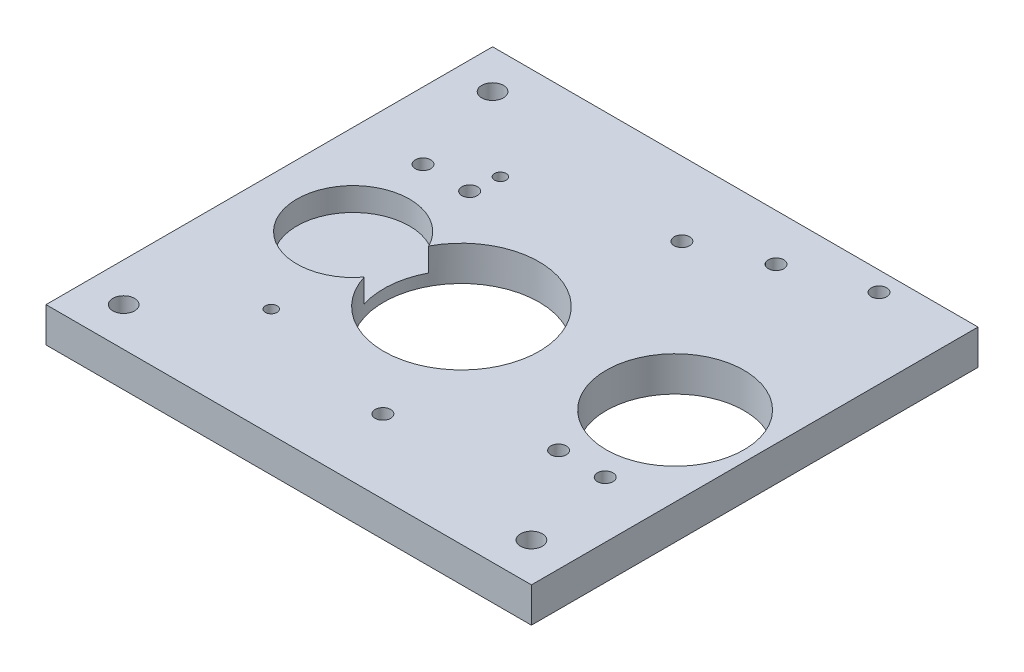
SolidWorks part; units mm, degrees
ref_plane "Front" through (0, 0, 0) normal (0, 0, 1) x (1, 0, 0)
ref_plane "Top" through (0, 0, 0) normal (0, 1, 0) x (1, 0, 0)
ref_plane "Right" through (0, 0, 0) normal (1, 0, 0) x (0, 0, -1)
sketch "Sketch1" plane through (0, 0, 0) normal (0, 1, 0) x (1, 0, 0)
  line L1 (0, 0) -> (125, 0)
  line L2 (0, 0) -> (0, 115)
  line L3 (0, 115) -> (125, 115)
  line L4 (125, 0) -> (125, 115)
  dimension "D1" = 125
  dimension "D2" = 115
extrude "Top_Base" add sketch "Sketch1" along normal blind 9
sketch "Fingers_Position" plane through (0, 9, 0) normal (0, 1, 0) x (1, 0, 0)
  line L0 (43.75, 76.5) -> (16.25, 76.5) construction
  line L1 (71.25, 60.5) -> (16.25, 60.5) construction
  line L2 (71.25, 60.5) -> (71.25, 92.5) construction
  line L3 (71.25, 92.5) -> (16.25, 92.5) construction
  line L4 (16.25, 60.5) -> (16.25, 92.5) construction
  line L5 (71.25, 22.5) -> (16.25, 22.5) construction
  line L6 (71.25, 22.5) -> (71.25, 54.5) construction
  line L7 (71.25, 54.5) -> (16.25, 54.5) construction
  line L8 (16.25, 22.5) -> (16.25, 54.5) construction
  line L9 (43.75, 92.5) -> (43.75, 60.5) construction
  line L10 (16.25, 38.5) -> (43.75, 38.5) construction
  line L12 (0, 115) -> (0, 0) construction
  line L13 (43.75, 54.5) -> (43.75, 22.5) construction
  line L14 (125, 57.5) -> (0, 57.5) construction
  line L15 (125, 0) -> (125, 115) construction
  line L16 (30, 38.5) -> (10, 38.5) construction
  line L17 (30, 38.5) -> (30, 18.5) construction
  circle A0 centre (30, 76.5) radius 20 construction
  circle A1 centre (30, 38.5) radius 20 construction
  circle A2 centre (30, 76.5) radius 20.5 construction
  circle A3 centre (30, 38.5) radius 20.5 construction
  circle A4 centre (30, 76.5) radius 19 construction
  circle A5 centre (30, 38.5) radius 19 construction
  dimension "D3" = 40
  dimension "D4" = 41
  dimension "D6" = 38
  dimension "D1" = 55
  dimension "D2" = 32
  dimension "D5" = 10
sketch "Intermediate_Gear_Position" plane through (0, 9, 0) normal (0, 1, 0) x (1, 0, 0)
  line L0 (11.25, 64.8419) -> (35.25, 64.8419) construction
  line L1 (23.25, 64.8419) -> (23.25, 46.8419) construction
  line L2 (35.25, 46.8419) -> (11.25, 46.8419) construction
  line L3 (71.25, 60.5) -> (71.25, 92.5) construction
  line L4 (35.25, 46.8419) -> (35.25, 82.8419) construction
  line L5 (92.5, 48.5) -> (116.5, 48.5) construction
  line L6 (35.25, 82.8419) -> (11.25, 82.8419) construction
  line L7 (11.25, 46.8419) -> (11.25, 82.8419) construction
  line L8 (104.5, 48.5) -> (104.5, 66.5) construction
  line L9 (125, 0) -> (125, 115) construction
  line L11 (88.5, 106.5) -> (120.5, 106.5) construction
  line L12 (120.5, 106.5) -> (120.5, 51.5) construction
  line L13 (120.5, 51.5) -> (88.5, 51.5) construction
  line L14 (88.5, 51.5) -> (88.5, 106.5) construction
  line L15 (92.5, 66.5) -> (92.5, 30.5) construction
  line L16 (92.5, 30.5) -> (116.5, 30.5) construction
  line L17 (116.5, 30.5) -> (116.5, 66.5) construction
  line L18 (116.5, 66.5) -> (92.5, 66.5) construction
  line L20 (104.5, 106.5) -> (104.5, 51.5) construction
  line L22 (125, 57.5) -> (0, 57.5) construction
  circle A0 centre (53.9231, 53.0493) radius 10 construction
  circle A3 centre (104.5, 57.5) radius 9 construction
  circle A4 centre (53.9231, 53.0493) radius 18 construction
  circle A6 centre (23.25, 55.8419) radius 12.8 construction
  circle A8 centre (53.9231, 53.0493) radius 9 construction
  circle A9 centre (104.5, 57.5) radius 17.75 construction
  circle A11 centre (30, 38.5) radius 19 construction
  point P19 (51.6343, 56.2752)
  point P31 (47.3502, 16.5234)
  point P36 (0, 0)
  point P39 (51.7268, 56)
  dimension "D3" = 20
  dimension "D4" = 18
  dimension "D5" = 33.5
  dimension "D2" = 36
  dimension "D6" = 25.6
  dimension "D17" = 35.5
  dimension "D7" = 24
  dimension "D8" = 36
  dimension "D9" = 32
  dimension "D10" = 55
  dimension "D11" = 24
  dimension "D12" = 36
  dimension "D13" = 40
  dimension "D14" = 20.5
  dimension "D15" = 36
sketch "Drive_Gear_Position" plane through (0, 9, 0) normal (0, 1, 0) x (1, 0, 0)
  line L21 (11.25, 64.8419) -> (35.25, 64.8419) construction
  circle A5 centre (23.25, 55.8419) radius 14 construction
  circle A7 centre (23.25, 55.8419) radius 13.5 construction
  dimension "D2" = 27
  dimension "D3" = 28
sketch "Sketch5" plane through (0, 9, 0) normal (0, 1, 0) x (1, 0, 0)
  circle A1 centre (23.25, 55.8419) radius 14.5
  dimension "D1" = 29
extrude "Drive_Gear_Extrude_Cut" cut sketch "Sketch5" against normal blind 6 contours A1
sketch "Sketch8" plane through (0, 9, 0) normal (0, 1, 0) x (1, 0, 0)
  line L0 (104.5, 106.5) -> (104.5, 51.5) construction
  circle A0 centre (104.5, 57.5) radius 9 construction
  circle A1 centre (104.5, 57.5) radius 17.75
  dimension "D1" = 18
  dimension "D2" = 35.5
sketch "Sketch17" plane through (0, 9, 0) normal (0, 1, 0) x (1, 0, 0)
  circle A0 centre (53.9231, 53.0493) radius 20
  dimension "D1" = 40
extrude "Intermediate_Gear_Top_Part_Cut" cut sketch "Sketch17" against normal through all
extrude "Thumb_Extrude_Cut" cut sketch "Sketch8" against normal through all
sketch "Thumb_Mount_Holes" plane through (0, 9, 0) normal (0, 1, 0) x (1, 0, 0)
  line L5 (104.5, 106.5) -> (104.5, 110) construction
  line L6 (88.5, 106.5) -> (85, 106.5) construction
  line L11 (85, 106.5) -> (85, 103) construction
  line L13 (116.5, 33.5) -> (110.5, 33.5) construction
  line L15 (110.5, 33.5) -> (110.5, 30.5) construction
  line L31 (92.5, 30.5) -> (116.5, 30.5) construction
  line L32 (116.5, 30.5) -> (116.5, 66.5) construction
  line L33 (104.5, 48.5) -> (104.5, 30.5) construction
  line L34 (92.5, 48.5) -> (116.5, 48.5) construction
  circle A11 centre (104.5, 110) radius 2
  circle A12 centre (85, 103) radius 2
  circle A13 centre (110.5, 33.5) radius 2
  circle A14 centre (98.5, 33.5) radius 2
  dimension "D3" = 6
  dimension "D2" = 4
  dimension "D5" = 4
  dimension "D1" = 3.5
  dimension "D4" = 3
sketch "Connect_Holes_Position" plane through (0, 9, 0) normal (0, 1, 0) x (1, 0, 0)
  line L0 (0, 115) -> (10, 115) construction
  line L1 (125, 115) -> (0, 115) construction
  line L2 (10, 115) -> (10, 105) construction
  line L3 (125, 0) -> (115, 0) construction
  line L4 (0, 0) -> (125, 0) construction
  line L5 (115, 0) -> (115, 10) construction
  line L7 (0, 115) -> (0, 0) construction
  line L12 (0, 0) -> (0, 10) construction
  line L13 (0, 10) -> (10, 10) construction
  circle A0 centre (10, 105) radius 2.8
  circle A1 centre (115, 10) radius 2.8
  circle A4 centre (10, 10) radius 2.8
  dimension "D5" = 5.6
  dimension "D1" = 10
  dimension "D2" = 10
  dimension "D3" = 10
  dimension "D4" = 10
  dimension "D8" = 10
  dimension "D9" = 10
sketch "Fingers_Mount_Holes" plane through (0, 9, 0) normal (0, 1, 0) x (1, 0, 0)
  line L0 (71.25, 92.5) -> (71.25, 96) construction
  line L1 (71.25, 96) -> (67.75, 96) construction
  line L2 (125, 57.5) -> (0, 57.5) construction
  line L3 (11.25, 79.8419) -> (17.25, 79.8419) construction
  line L4 (11.25, 46.8419) -> (11.25, 82.8419) construction
  line L5 (17.25, 79.8419) -> (17.25, 82.8419) construction
  line L6 (35.25, 82.8419) -> (11.25, 82.8419) construction
  line L7 (23.25, 64.8419) -> (23.25, 82.8419) construction
  circle A0 centre (67.75, 96) radius 2
  circle A1 centre (67.75, 19) radius 2
  circle A2 centre (17.25, 79.8419) radius 2
  circle A3 centre (29.25, 79.8419) radius 2
  dimension "D3" = 4
  dimension "D4" = 4
  dimension "D1" = 3.5
  dimension "D2" = 3.5
  dimension "D5" = 6
  dimension "D6" = 3
sketch "Sketch26" plane through (0, 0, 0) normal (0, -1, 0) x (1, 0, 0)
  line L0 (30, -18) -> (30, -28) construction
  line L1 (30, -38.5) -> (30, -18.5) construction
  line L2 (0, -57.5) -> (125, -57.5) construction
  circle A0 centre (30, -38.5) radius 20.5 construction
  circle A1 centre (30, -28) radius 1.5
  circle A2 centre (30, -87) radius 1.5
  dimension "D2" = 3
  dimension "D1" = 10
extrude "String_Holes" cut sketch "Sketch26" against normal through all
extrude "Thumb_Mount_Holes_(M4)" cut sketch "Thumb_Mount_Holes" against normal through all
extrude "Fingers_Mount_Holes_(M4)" cut sketch "Fingers_Mount_Holes" against normal through all
extrude "Connect_Holes_(M6)" cut sketch "Connect_Holes_Position" against normal through all
sketch "Sketch27" plane through (0, 0, 0) normal (0, -1, 0) x (1, 0, 0)
  circle A0 centre (29.25, -79.8419) radius 3.75
  circle A1 centre (17.25, -79.8419) radius 3.75
  dimension "D1" = 7.5
extrude "XL320_Nut_(M4)" cut sketch "Sketch27" against normal blind 4
